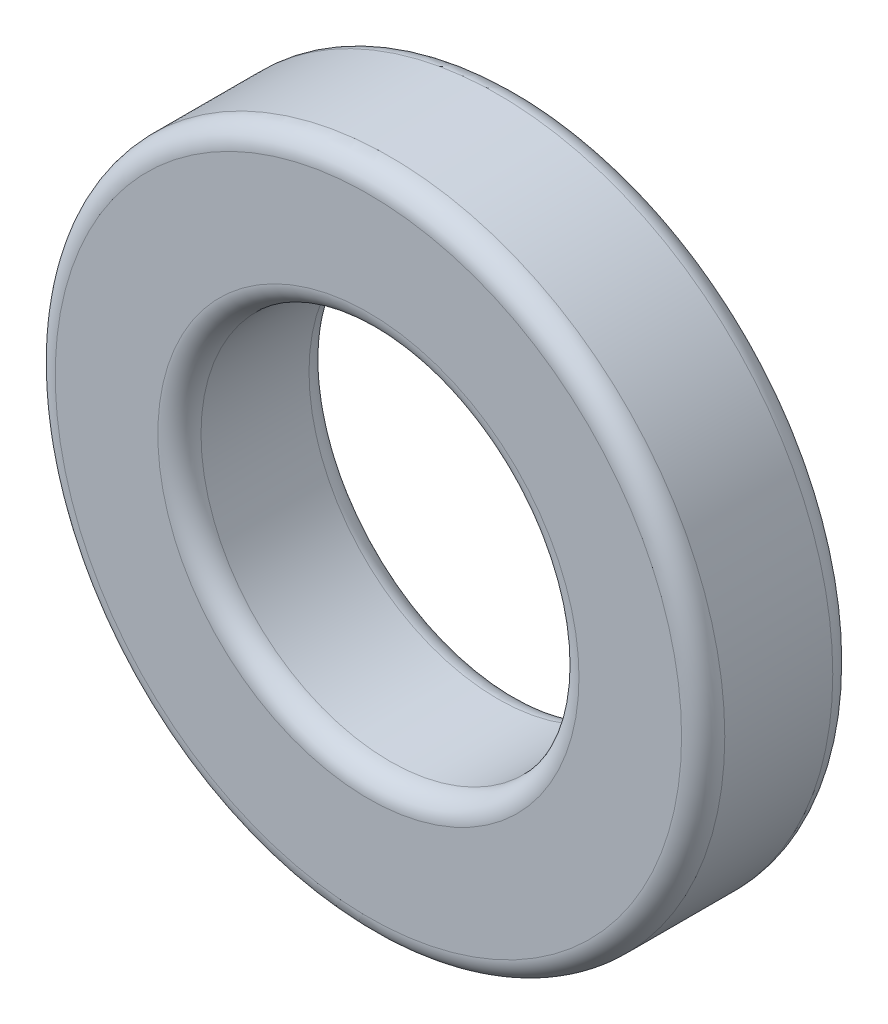
SolidWorks part; units mm, degrees
ref_plane "前视基准面" through (0, 0, 0) normal (0, 0, 1) x (1, 0, 0)
ref_plane "上视基准面" through (0, 0, 0) normal (0, 1, 0) x (1, 0, 0)
ref_plane "右视基准面" through (0, 0, 0) normal (1, 0, 0) x (0, 0, -1)
sketch "草图1" plane through (0, 0, 0) normal (0, 0, 1) x (1, 0, 0)
  circle A0 centre (0, 0) radius 17.5
  circle A1 centre (0, 0) radius 31
  dimension "D1" = 35
  dimension "D2" = 62
extrude "凸台-拉伸1" add sketch "草图1" along normal blind 14
fillet "圆角2" radius 2 4 edges at (17.5, 0, 0) (31, 0, 0) (17.5, 0, 14) (31, 0, 14)
